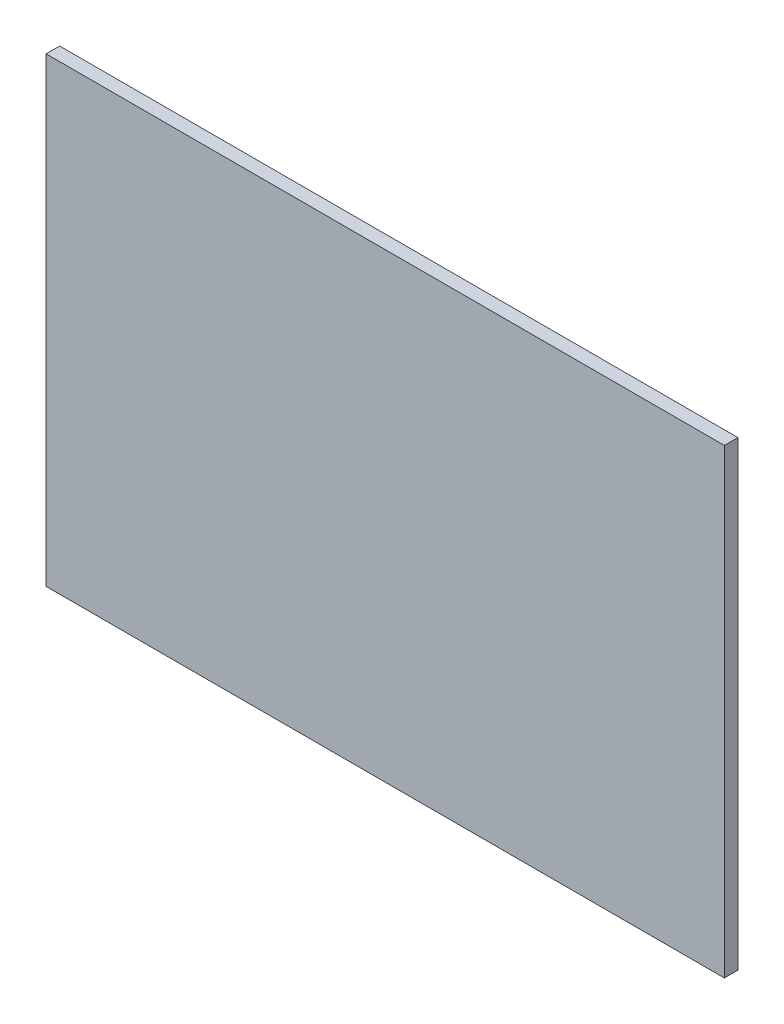
SolidWorks part; units mm, degrees
ref_plane "Alzado" through (0, 0, 0) normal (0, 0, 1) x (1, 0, 0)
ref_plane "Planta" through (0, 0, 0) normal (0, 1, 0) x (1, 0, 0)
ref_plane "Vista lateral" through (0, 0, 0) normal (1, 0, 0) x (0, 0, -1)
sketch "Croquis1" plane through (0, 0, 0) normal (0, 0, 1) x (1, 0, 0)
  line L1 (-50, -34) -> (50, -34)
  line L2 (-50, -34) -> (-50, 34)
  line L3 (-50, 34) -> (50, 34)
  line L4 (50, -34) -> (50, 34)
  line L5 (-50, -34) -> (50, 34) construction
  line L6 (-50, 34) -> (50, -34) construction
  point P0 (0, 0)
  dimension "D1" = 100
  dimension "D2" = 68
extrude "Saliente-Extruir1" add sketch "Croquis1" along normal blind 2
